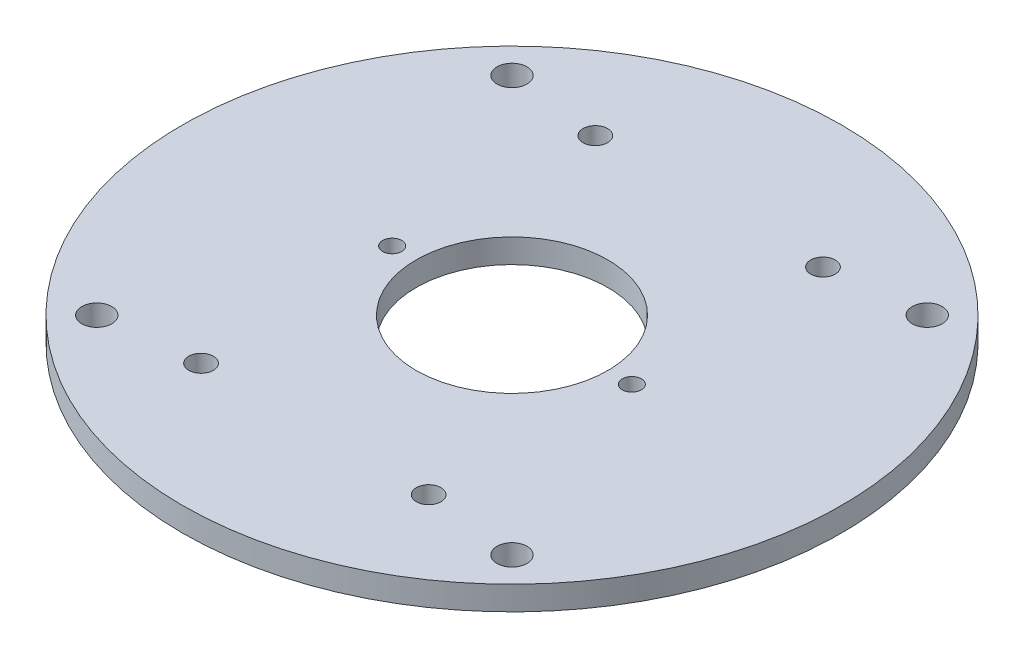
SolidWorks part; units mm, degrees
ref_plane "前视基准面" through (0, 0, 0) normal (0, 0, 1) x (1, 0, 0)
ref_plane "上视基准面" through (0, 0, 0) normal (0, 1, 0) x (1, 0, 0)
ref_plane "右视基准面" through (0, 0, 0) normal (1, 0, 0) x (0, 0, -1)
sketch "草图1" plane through (0, 0, 0) normal (0, 1, 0) x (1, 0, 0)
  circle A0 centre (0, 0) radius 27.5
  dimension "D1" = 55
extrude "凸台-拉伸1" add sketch "草图1" along normal blind 2
ref_plane "上表面" through (0, 2, 0) normal (0, 1, 0) x (1, 0, 0)
sketch "草图2" plane through (0, 2, 0) normal (0, 1, 0) x (1, 0, 0)
  circle A0 centre (0, 0) radius 8
  point P0 (0, 0)
  dimension "D1" = 16
extrude "切除-拉伸1" cut sketch "草图2" against normal through all
hole_wizard "M2 螺纹孔1" positions "草图10" profile "草图11" tap size "M2" standard "GB" end condition through all
sketch "草图10" plane through (0, 2, 0) normal (0, 1, 0) x (1, 0, 0)
  point P0 (-10, 0)
  point P1 (0, 0)
sketch "草图11" plane through (-10, 2, 0) normal (1, 0, 0) x (0, 0, 1)
  line L0 (0, 0) -> (0, 2)
  line L1 (0, 2) -> (0.8, 2)
  line L2 (0.8, 2) -> (0.8, 0)
  line L5 (0.8, 0) -> (0, 0)
  line L11 (0, -6.35) -> (0, 107.95) construction
  dimension "通孔螺纹孔钻头直径" = 1.6
  dimension "通孔螺纹孔钻头深度" = 2
cosmetic thread "孔螺蚊线4" parameters "D2"=2
ref_plane "基准面1" through (0, 0, 0) normal (1, 0, 0) x (0, 0, -1)
ref_plane "基准面2" through (0, 0, 0) normal (0, 0, 1) x (1, 0, 0)
hole_wizard "M3 螺纹孔4" positions "草图14" profile "草图15" tap size "M3" standard "GB" end condition through all
sketch "草图14" plane through (0, 2, 0) normal (0, 1, 0) x (1, 0, 0)
  line L1 (-24.4994, 24.4994) -> (24.8529, -24.8529) construction
  line L3 (0, -55) -> (0, 55) construction
  circle A0 centre (0, 0) radius 24.5
  point P0 (-17.3241, 17.3241)
  dimension "D1" = 45
sketch "草图15" plane through (-17.3241, 2, -17.3241) normal (1, 0, 0) x (0, 0, 1)
  line L0 (0, 0) -> (0, 2)
  line L1 (0, 2) -> (1.25, 2)
  line L2 (1.25, 2) -> (1.25, 0)
  line L5 (1.25, 0) -> (0, 0)
  line L11 (0, -6.35) -> (0, 107.95) construction
  dimension "通孔螺纹孔钻头直径" = 2.5
  dimension "通孔螺纹孔钻头深度" = 2
cosmetic thread "孔螺蚊线6" parameters "D2"=3
mirror "镜向1" about plane through (0, 0, 0) normal (1, 0, 0) of "M3 螺纹孔4"
mirror "镜向2" about plane through (0, 0, 0) normal (0, 0, 1) of "镜向1", "M3 螺纹孔4"
mirror "镜向3" about plane through (0, 0, 0) normal (1, 0, 0) of "M2 螺纹孔1"
hole_wizard "M2.5 螺纹孔1" positions "草图16" profile "草图17" tap size "M2.5" standard "GB" end condition through all
sketch "草图16" plane through (0, 2, 0) normal (0, 1, 0) x (1, 0, 0)
  line L0 (-9.4971, 16.4517) -> (0, 0) construction
  line L1 (0, 0) -> (19.2292, -33.3105) construction
  line L3 (0, 0) -> (32.4089, 18.7088) construction
  line L6 (-9.4971, 16.4517) -> (40.862, 16.4517) construction
  point P0 (-9.4971, 16.4517)
  point P9 (9.4971, 16.4517)
  point P41 (0, 0)
  dimension "D1" = 18.9961
  dimension "D2" = 9.5
  dimension "D3" = 16.45
sketch "草图17" plane through (-9.4971, 2, -16.4517) normal (1, 0, 0) x (0, 0, 1)
  line L0 (0, 0) -> (0, 2)
  line L1 (0, 2) -> (1.025, 2)
  line L2 (1.025, 2) -> (1.025, 0)
  line L5 (1.025, 0) -> (0, 0)
  line L11 (0, -6.35) -> (0, 107.95) construction
  dimension "通孔螺纹孔钻头直径" = 2.05
  dimension "通孔螺纹孔钻头深度" = 2
cosmetic thread "孔螺蚊线7" parameters "D2"=2.5
cosmetic thread "孔螺蚊线8" parameters "D2"=2.5
mirror "镜向4" about plane through (0, 0, 0) normal (0, 0, 1) of "M2.5 螺纹孔1"
